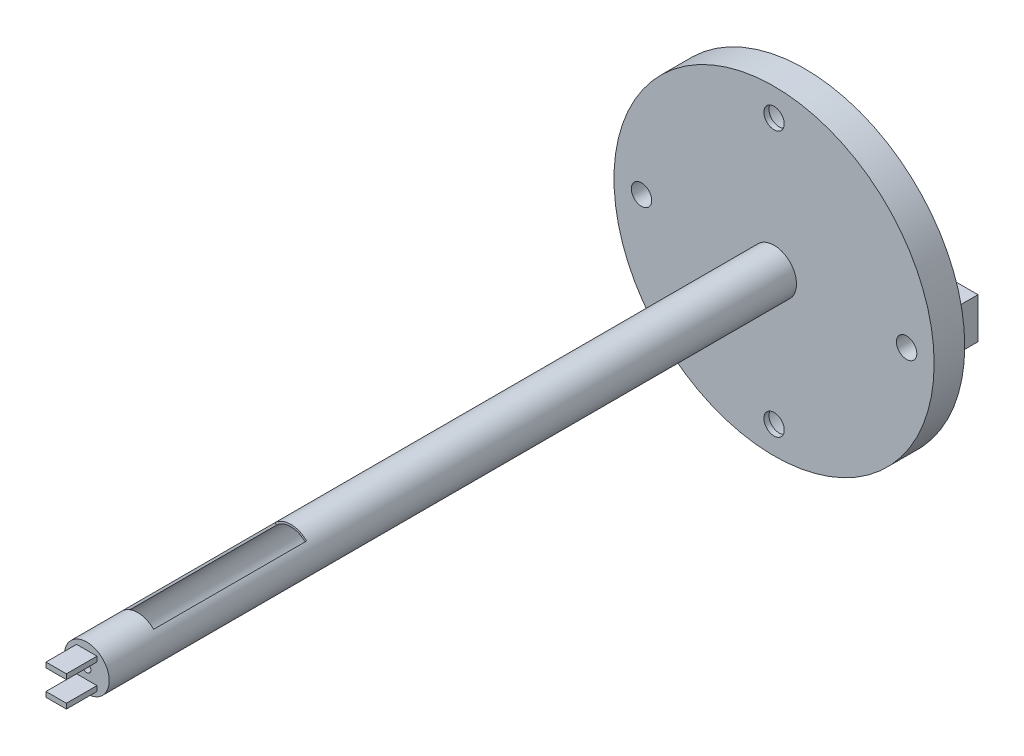
SolidWorks part; units mm, degrees
ref_plane "前视基准面" through (0, 0, 0) normal (0, 0, 1) x (1, 0, 0)
ref_plane "上视基准面" through (0, 0, 0) normal (0, 1, 0) x (1, 0, 0)
ref_plane "右视基准面" through (0, 0, 0) normal (1, 0, 0) x (0, 0, -1)
sketch "草图1" plane through (0, 0, 0) normal (0, 0, 1) x (1, 0, 0)
  circle A0 centre (0, 0) radius 15.7
extrude "凸台-拉伸1" add sketch "草图1" along normal blind 3
sketch "草图5" plane through (0, 0, 0) normal (0, 0, -1) x (-1, 0, 0)
  circle A0 centre (13, 0) radius 1
  point P0 (13, 0)
extrude "切除-拉伸3" cut sketch "草图5" against normal blind 3
sketch "草图6" plane through (0, 0, 0) normal (0, 0, -1) x (-1, 0, 0)
  circle A0 centre (-13, 0) radius 1
  point P0 (-13, 0)
extrude "切除-拉伸4" cut sketch "草图6" against normal blind 3
sketch "草图7" plane through (0, 0, 0) normal (0, 0, -1) x (-1, 0, 0)
  circle A0 centre (0, 0) radius 2
extrude "切除-拉伸5" cut sketch "草图7" against normal blind 3
sketch "草图10" plane through (0, 0, 0) normal (0, 0, -1) x (-1, 0, 0)
  line L0 (-2, 2) -> (-2, -2)
  line L1 (-2, 2) -> (-14, 2)
  line L2 (-2, -2) -> (-14, -2)
  line L3 (-14, 2) -> (-14, -2)
extrude "凸台-拉伸8" add sketch "草图10" along normal blind 3 separate body
sketch "草图11" plane through (0, 0, 0) normal (0, 0, -1) x (-1, 0, 0)
  line L0 (2, 2) -> (2, -2)
  line L1 (2, 2) -> (14, 2)
  line L2 (2, -2) -> (14, -2)
  line L3 (14, 2) -> (14, -2)
extrude "凸台-拉伸9" add sketch "草图11" along normal blind 3 separate body
sketch "草图12" plane through (0, 0, 3) normal (0, 0, 1) x (1, 0, 0)
  circle A0 centre (0, 0) radius 2.2
extrude "凸台-拉伸11" add sketch "草图12" along normal blind 47.4
sketch "草图16" plane through (0, 0, 3) normal (0, 0, -1) x (-1, 0, 0)
  circle A0 centre (0, 0) radius 2
extrude "切除-拉伸6" cut sketch "草图16" against normal blind 47.4
sketch "草图19" plane through (0, 0, 50.4) normal (0, 0, 1) x (1, 0, 0)
  line L0 (0, 0) -> (1.5556, 1.5556)
  line L1 (0, 0) -> (-1.5556, 1.5556)
  line L2 (0, 0) -> (1.4142, 1.4142)
  line L3 (0, 0) -> (-1.4142, 1.4142)
  line L4 (0, -2) -> (0, -2.2)
  circle A0 centre (0, 0) radius 2 construction
  circle A1 centre (0, 0) radius 2.2 construction
  circle A2 centre (0, 0) radius 2.2 construction
  arc A3 (-1.4142, 1.4142) -> (0, -2) centre (0, 0) ccw
  arc A4 (1.4142, 1.4142) -> (0, -2) centre (0, 0) cw
  arc A5 (0, -2.2) -> (1.5556, 1.5556) centre (0, 0) ccw
  arc A6 (0, -2.2) -> (-1.5556, 1.5556) centre (0, 0) cw
  point P0 (0, -2)
  point P1 (0, -2.2)
  circle M2 centre (0, 0) radius 2
  circle M3 centre (0, 0) radius 2.2
extrude "凸台-拉伸13" add sketch "草图19" along normal blind 15 contours L4 L1 M2 M3 | L4 L0 M2 M3
sketch "草图20" plane through (0, 0, 65.4) normal (0, 0, 1) x (1, 0, 0)
  circle A0 centre (0, 0) radius 2.2
extrude "凸台-拉伸15" add sketch "草图20" along normal blind 8
sketch "草图22" plane through (0, 0, 73.4) normal (0, 0, 1) x (1, 0, 0)
  line L0 (1, 1.5) -> (-1, 1.5)
  line L1 (1, 1.5) -> (1, 1)
  line L2 (-1, 1.5) -> (-1, 1)
  line L3 (1, 1) -> (-1, 1)
  line L4 (1, -1) -> (-1, -1)
  line L5 (1, -1) -> (1, -1.5)
  line L6 (-1, -1) -> (-1, -1.5)
  line L7 (1, -1.5) -> (-1, -1.5)
extrude "切除-拉伸7" cut sketch "草图22" against normal blind 3 flip side to cut
sketch "草图24" plane through (0, 0, 70.4) normal (0, 0, 1) x (1, 0, 0)
  circle A0 centre (0, 0) radius 0.4
extrude "切除-拉伸9" cut sketch "草图24" against normal blind 5
sketch "草图25" plane through (0, 0, 3) normal (0, 0, 1) x (1, 0, 0)
  circle A0 centre (0, 13) radius 1
  circle A1 centre (0, -13) radius 1
extrude "切除-拉伸10" cut sketch "草图25" against normal blind 0.5
sketch "草图26" plane through (0, 0, 2.5) normal (0, 0, 1) x (1, 0, 0)
  circle A0 centre (0, 13) radius 2.5
  circle A1 centre (0, -13) radius 2.5
extrude "切除-拉伸12" cut sketch "草图26" against normal blind 2.5
sketch "草图27" plane through (0, 0, -3) normal (0, 0, -1) x (-1, 0, 0)
  circle A0 centre (8, 0) radius 1
  circle A1 centre (-8, 0) radius 1
extrude "切除-拉伸13" cut sketch "草图27" against normal blind 5
